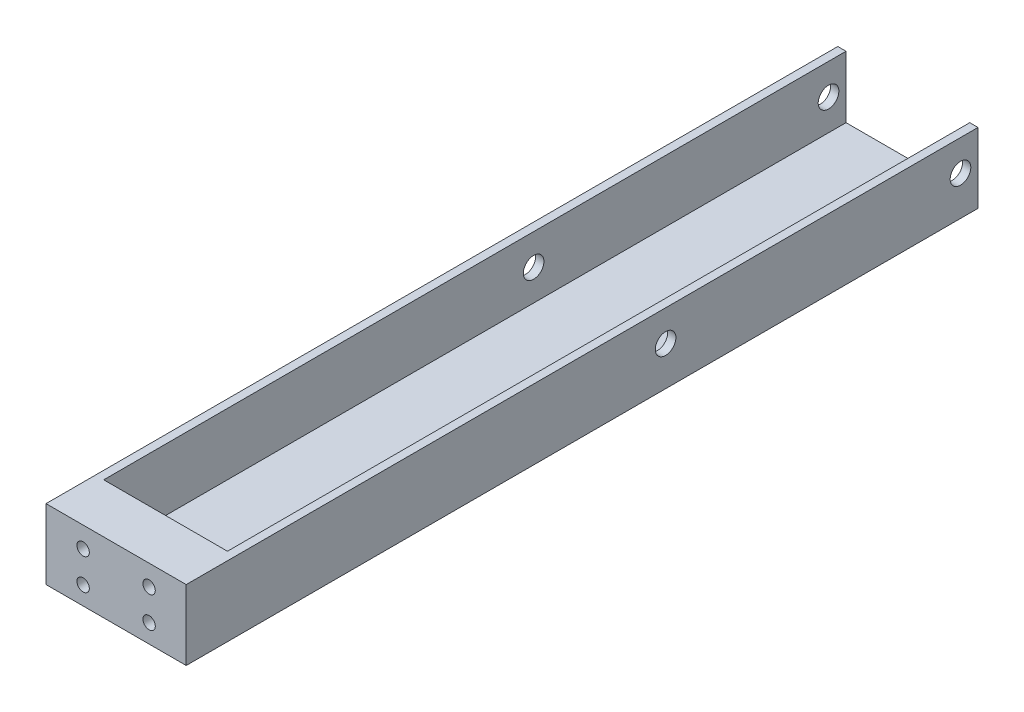
SolidWorks part; units mm, degrees
ref_plane "Front Plane" through (0, 0, 0) normal (0, 0, 1) x (1, 0, 0)
ref_plane "Top Plane" through (0, 0, 0) normal (0, 1, 0) x (1, 0, 0)
ref_plane "Right Plane" through (0, 0, 0) normal (1, 0, 0) x (0, 0, -1)
sketch "Sketch1" plane through (0, 0, 0) normal (0, 0, 1) x (1, 0, 0)
  line L1 (15, 7.5) -> (-15, 7.5)
  line L2 (15, 7.5) -> (15, -7.5)
  line L3 (15, -7.5) -> (-15, -7.5)
  line L4 (-15, 7.5) -> (-15, -7.5)
  line L5 (15, 7.5) -> (-15, -7.5) construction
  line L6 (15, -7.5) -> (-15, 7.5) construction
  point P1 (0, 0)
  dimension "D1" = 30
  dimension "D2" = 15
extrude "Boss-Extrude1" add sketch "Sketch1" along normal blind 180
sketch "Sketch3" plane through (15, 0, 0) normal (1, 0, 0) x (0, 0, -1)
  circle A0 centre (-4.2453, 0) radius 2.5
  dimension "D1" = 5
shell "Shell2" thickness 2
extrude "Cut-Extrude3" cut sketch "Sketch3" against normal blind 50
ref_plane "Plane1" through (0, 0, 40) normal (0, 0, 1) x (1, 0, 0)
mirror "Mirror1" about plane through (0, 0, 40) normal (0, 0, 1) of "Cut-Extrude3"
mirror "Mirror3" about plane through (0, 0, 0) normal (1, 0, 0) of "Mirror1", "Cut-Extrude3"
sketch3d "3DSketch1" plane through (0, 0, 0) normal (0, 0, 1) x (1, 0, 0)
sketch "Sketch7" plane through (0, 0, 182) normal (0, 0, 1) x (1, 0, 0)
  line L0 (-17, 7.5) -> (-17, -9.5)
  line L1 (-17, 7.5) -> (17, 7.5)
  line L2 (-17, -9.5) -> (17, -9.5)
  line L3 (17, 7.5) -> (17, -9.5)
extrude "Boss-Extrude5" add sketch "Sketch7" along normal blind 10
sketch "Sketch12" plane through (0, 0, 192) normal (0, 0, 1) x (1, 0, 0)
  circle A0 centre (-8, 2.5) radius 1.5
  circle A1 centre (-8, -5.0543) radius 1.5
  circle A2 centre (8, 2.5) radius 1.5
sketch "Sketch13" plane through (0, 0, 192) normal (0, 0, 1) x (1, 0, 0)
  circle A0 centre (8, -5) radius 1.5
extrude "Cut-Extrude5" cut sketch "Sketch12" against normal through all
extrude "Cut-Extrude6" cut sketch "Sketch13" against normal through all contours A0
